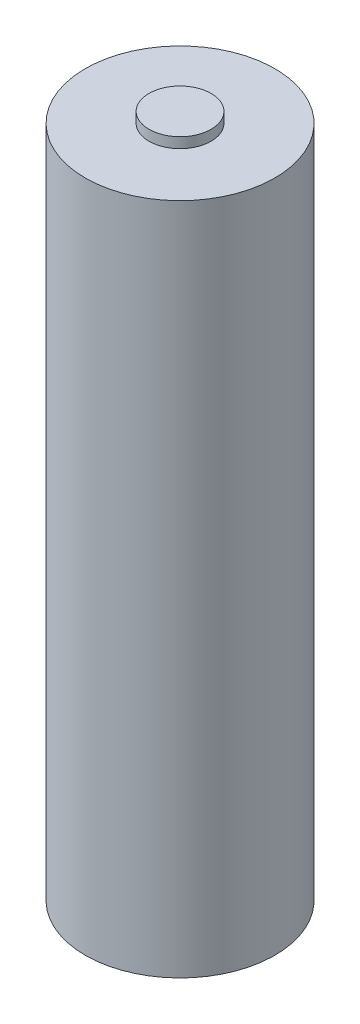
SolidWorks part; units mm, degrees
ref_plane "前视基准面" through (0, 0, 0) normal (0, 0, 1) x (1, 0, 0)
ref_plane "上视基准面" through (0, 0, 0) normal (0, 1, 0) x (1, 0, 0)
ref_plane "右视基准面" through (0, 0, 0) normal (1, 0, 0) x (0, 0, -1)
other "Configuration Table"
sketch "草图1" plane through (0, 0, 0) normal (0, 1, 0) x (1, 0, 0)
  circle A0 centre (0, 0) radius 9.15
  dimension "D1" = 18.3
extrude "凸台-拉伸1" add sketch "草图1" along normal blind 65
sketch "草图2" plane through (0, 65, 0) normal (0, 1, 0) x (1, 0, 0)
  circle A0 centre (0, 0) radius 3
  dimension "D1" = 6
extrude "凸台-拉伸2" add sketch "草图2" along normal blind 1
